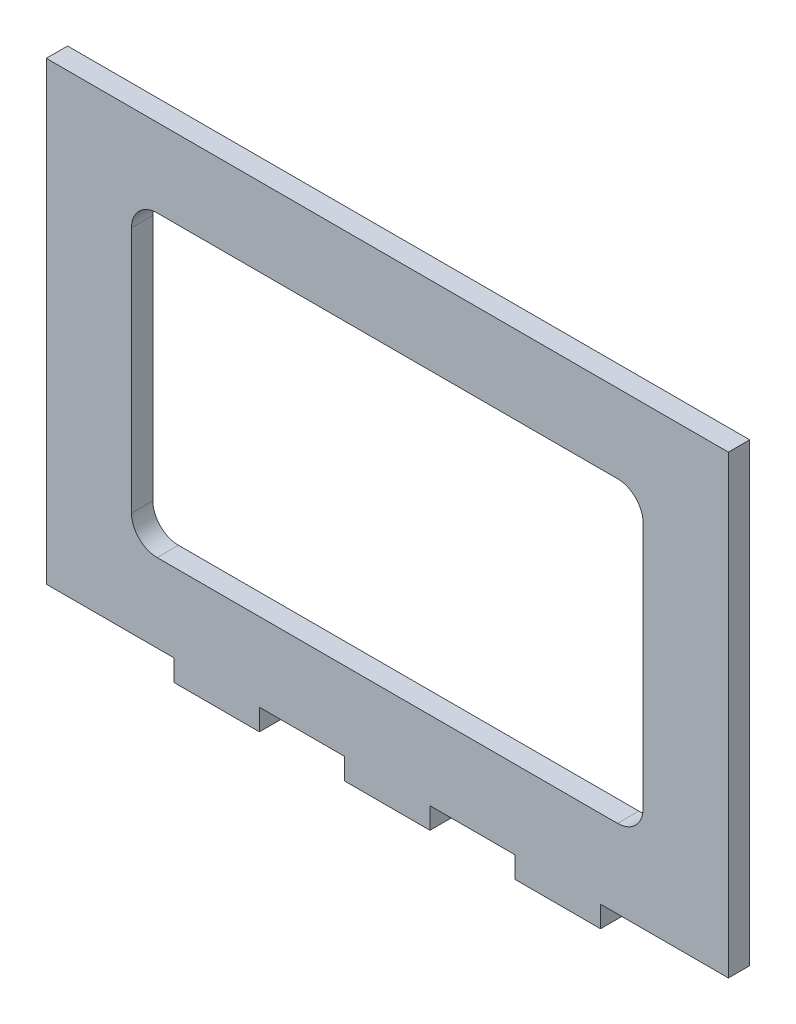
SolidWorks part; units mm, degrees
material "Beech"
ref_plane "Front" through (0, 0, 0) normal (0, 0, 1) x (1, 0, 0)
ref_plane "Top" through (0, 0, 0) normal (0, 1, 0) x (1, 0, 0)
ref_plane "Right" through (0, 0, 0) normal (1, 0, 0) x (0, 0, -1)
sketch "Sketch1" plane through (0, 0, 0) normal (0, 0, 1) x (1, 0, 0)
  line L0 (-40, -26.705) -> (-25, -26.705)
  line L1 (-40, -26.705) -> (40, -26.705) construction
  line L2 (-40, -26.705) -> (-40, 26.705)
  line L3 (-40, 26.705) -> (40, 26.705)
  line L4 (40, -26.705) -> (40, 26.705)
  line L5 (-40, -26.705) -> (40, 26.705) construction
  line L6 (-40, 26.705) -> (40, -26.705) construction
  line L7 (-27, -17.5) -> (27, -17.5)
  line L8 (-30, -14.5) -> (-30, 14.5)
  line L9 (-27, 17.5) -> (27, 17.5)
  line L10 (30, -14.5) -> (30, 14.5)
  line L11 (-30, -17.5) -> (30, 17.5) construction
  line L12 (-30, 17.5) -> (30, -17.5) construction
  line L13 (-25, -26.705) -> (-25, -29.205)
  line L14 (-25, -29.205) -> (-15, -29.205)
  line L15 (-15, -29.205) -> (-15, -26.705)
  line L16 (-15, -26.705) -> (-5, -26.705)
  line L17 (-5, -26.705) -> (-5, -29.205)
  line L18 (-5, -29.205) -> (5, -29.205)
  line L19 (5, -29.205) -> (5, -26.705)
  line L20 (5, -26.705) -> (15, -26.705)
  line L21 (15, -26.705) -> (15, -29.205)
  line L22 (15, -29.205) -> (25, -29.205)
  line L23 (25, -29.205) -> (25, -26.705)
  line L24 (25, -26.705) -> (35, -26.705)
  line L25 (40, -26.705) -> (35, -26.705)
  arc A0 (27, -17.5) -> (30, -14.5) centre (27, -14.5) ccw
  arc A1 (-27, -17.5) -> (-30, -14.5) centre (-27, -14.5) cw
  arc A2 (-30, 14.5) -> (-27, 17.5) centre (-27, 14.5) cw
  arc A3 (27, 17.5) -> (30, 14.5) centre (27, 14.5) cw
  point P0 (0, 0)
  point P6 (0, 0)
  dimension "D5" = 3
  dimension "D1" = 53.41
  dimension "D2" = 80
  dimension "D3" = 35
  dimension "D4" = 60
  dimension "D6" = 15
  dimension "D7" = 10
  dimension "D8" = 2.5
  dimension "D9" = 3
extrude "Boss-Extrude1" add sketch "Sketch1" along normal blind 2.5 contours L1 L4 L3 L2 L9 A3 L10 A0 L7 A1 L8 A2
